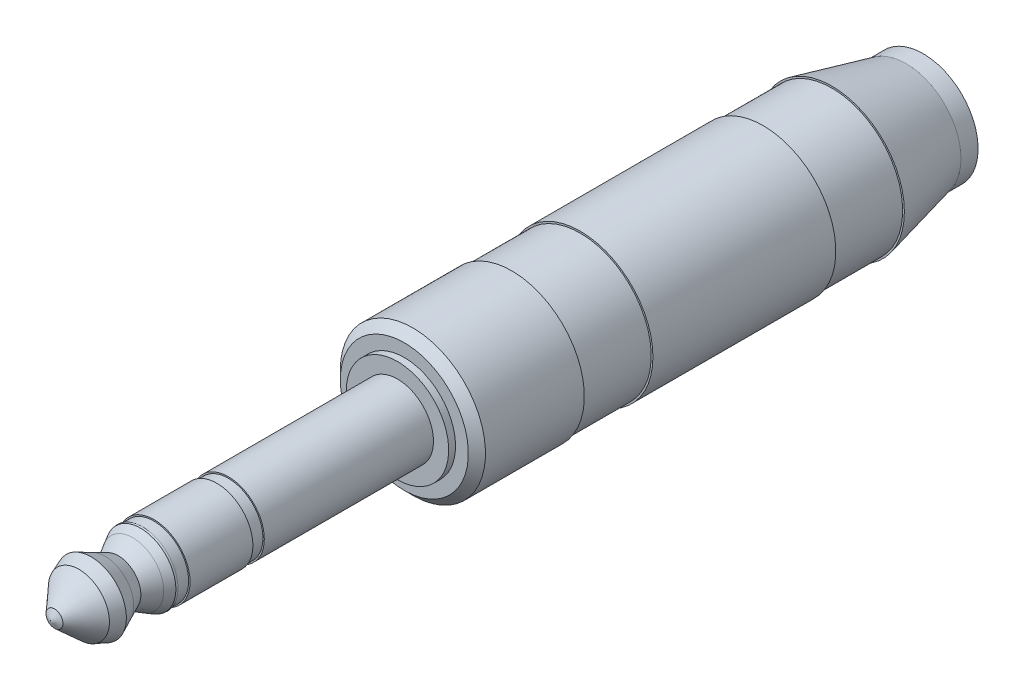
SolidWorks part; units mm, degrees
ref_plane "Front Plane" through (0, 0, 0) normal (1, 0, 0) x (0, 1, 0)
ref_plane "Top Plane" through (0, 0, 0) normal (0, 0, 1) x (0, 1, 0)
ref_plane "Right Plane" through (0, 0, 0) normal (0, 1, 0) x (-1, 0, 0)
sketch "Sketch1" plane through (0, 0, 0) normal (0, 1, 0) x (-1, 0, 0)
  line L0 (0, 30.34) -> (-0.74, 30.01)
  line L1 (-0.74, 30.01) -> (-2.67, 27.87)
  line L2 (-2.67, 27.87) -> (-3.08, 26.8)
  line L3 (-3.08, 26.8) -> (-2.51, 25.58)
  line L4 (-2.51, 25.58) -> (-1.98, 24.43)
  line L5 (-1.98, 24.43) -> (-2.7, 23.15)
  line L6 (-2.7, 23.15) -> (-3.08, 22.47)
  line L7 (-3.08, 22.47) -> (-3.15, 21.84)
  line L8 (-3.15, 21.84) -> (-3.15, 0)
  line L9 (-3.15, 0) -> (-4.48, 0)
  line L10 (-4.48, 0) -> (-4.48, -0.6)
  line L11 (-4.48, -0.6) -> (-5.6, -0.6)
  line L12 (-5.6, -0.6) -> (-6.35, -1.35)
  line L13 (-6.35, -1.35) -> (-6.35, -38)
  line L14 (-6.35, -38) -> (-4.8, -44.5)
  line L15 (-4.8, -44.5) -> (-4.8, -46)
  line L16 (-4.8, -46) -> (0, -46)
  line L17 (0, -46) -> (0, 30.34)
  line L18 (0, -200) -> (0, 200) construction
revolve "Body" add sketch "Sketch1" angle 360 about L18
sketch "Sketch2" plane through (0, 0, 0) normal (0, 1, 0) x (-1, 0, 0)
  line L0 (-3.03, 21.3) -> (-3.4, 21.3)
  line L1 (-3.4, 21.3) -> (-3.4, 22.3)
  line L2 (-3.4, 22.3) -> (-3.03, 22.3)
  line L3 (-3.03, 22.3) -> (-3.03, 21.3)
  line L4 (-3.03, 14.8) -> (-3.4, 14.8)
  line L5 (-3.4, 14.8) -> (-3.4, 15.8)
  line L6 (-3.4, 15.8) -> (-3.03, 15.8)
  line L7 (-3.03, 15.8) -> (-3.03, 14.8)
  line L8 (0, -200) -> (0, 200) construction
revolve "Insulators" cut sketch "Sketch2" angle 360 about L8
sketch "Sketch3" plane through (0, 0, 0) normal (0, 1, 0) x (-1, 0, 0)
  line L0 (-6.2, -10) -> (-6.6, -10)
  line L1 (-6.6, -10) -> (-6.6, -16)
  line L2 (-6.6, -16) -> (-6.2, -16)
  line L3 (-6.2, -16) -> (-6.2, -10)
  line L4 (-6.2, -32) -> (-6.6, -32)
  line L5 (-6.6, -32) -> (-6.6, -38)
  line L6 (-6.6, -38) -> (-6.2, -38)
  line L7 (-6.2, -38) -> (-6.2, -32)
  line L8 (0, -200) -> (0, 200) construction
revolve "Grip" cut sketch "Sketch3" angle 360 about L8
sketch "Sketch4" plane through (0, 0, 0) normal (0, 1, 0) x (-1, 0, 0)
  line L0 (0, -46.5) -> (-3.1, -46.5)
  line L1 (-3.1, -46.5) -> (-3.1, -42)
  line L2 (-3.1, -42) -> (0, -42)
  line L3 (0, -42) -> (0, -46.5)
  line L4 (0, -200) -> (0, 200) construction
revolve "CableBore" cut sketch "Sketch4" angle 360 about L4
